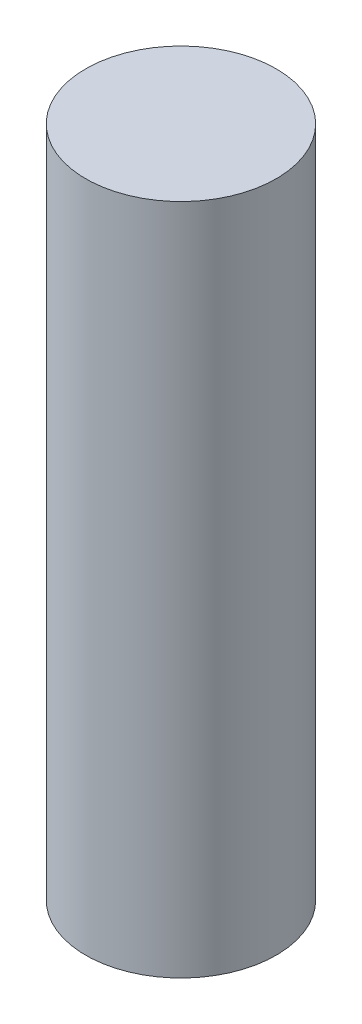
SolidWorks part; units mm, degrees
ref_plane "Front Plane" through (0, 0, 0) normal (0, 0, 1) x (1, 0, 0)
ref_plane "Top Plane" through (0, 0, 0) normal (0, 1, 0) x (1, 0, 0)
ref_plane "Right Plane" through (0, 0, 0) normal (1, 0, 0) x (0, 0, -1)
sketch "Sketch1" plane through (0, 0, 0) normal (0, 1, 0) x (1, 0, 0)
  circle A0 centre (0, 0) radius 10.795
  dimension "D1" = 21.59
extrude "Boss-Extrude1" add sketch "Sketch1" along normal blind 76.2
